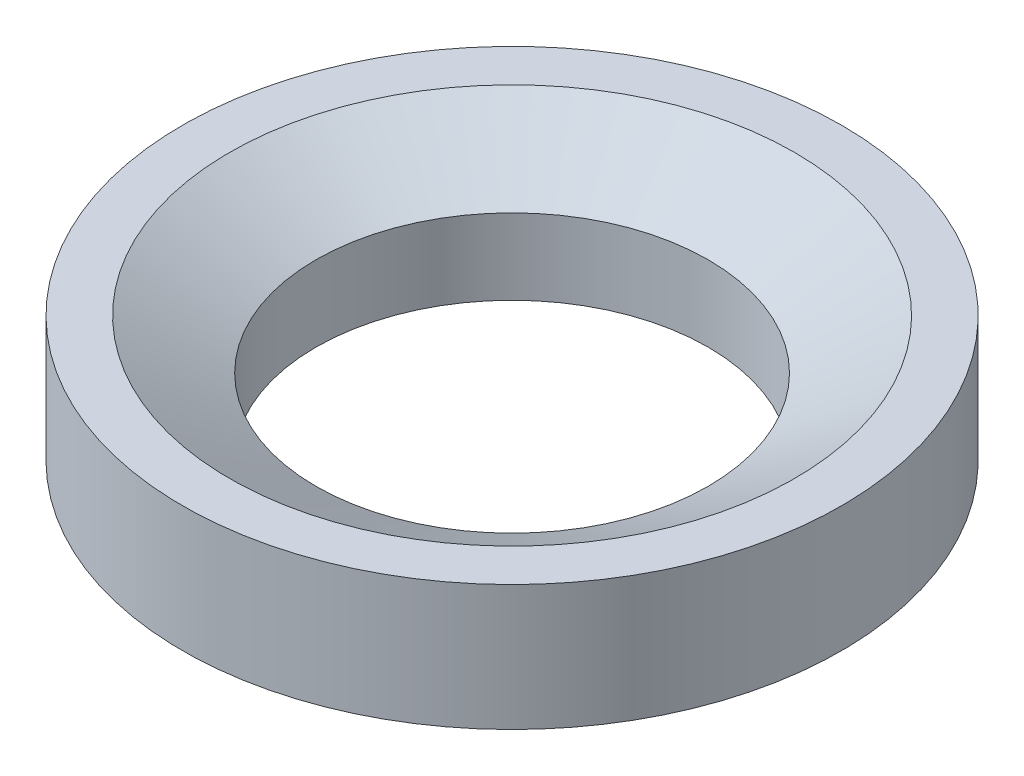
SolidWorks part; units mm, degrees
ref_plane "前视基准面" through (0, 0, 0) normal (0, 0, 1) x (1, 0, 0)
ref_plane "上视基准面" through (0, 0, 0) normal (0, 1, 0) x (1, 0, 0)
ref_plane "右视基准面" through (0, 0, 0) normal (1, 0, 0) x (0, 0, -1)
sketch "草图2" plane through (0, 0, 0) normal (1, 0, 0) x (0, 0, -1)
  line L3 (0, -2) -> (0, 2) construction
  line L5 (-10.5, 2) -> (-9, 2)
  line L6 (-9, 2) -> (-6.25, 0.4123)
  line L7 (-6.25, 0.4123) -> (-6.25, -2)
  line L8 (-6.25, -2) -> (-10.5, -2)
  line L9 (-10.5, -2) -> (-10.5, 2)
  point P3 (0, 0)
  dimension "D1" = 60
  dimension "D2" = 4
  dimension "D3" = 21
  dimension "D4" = 18
  dimension "D5" = 12.5
revolve "旋转1" add sketch "草图2" angle 360 about L3
